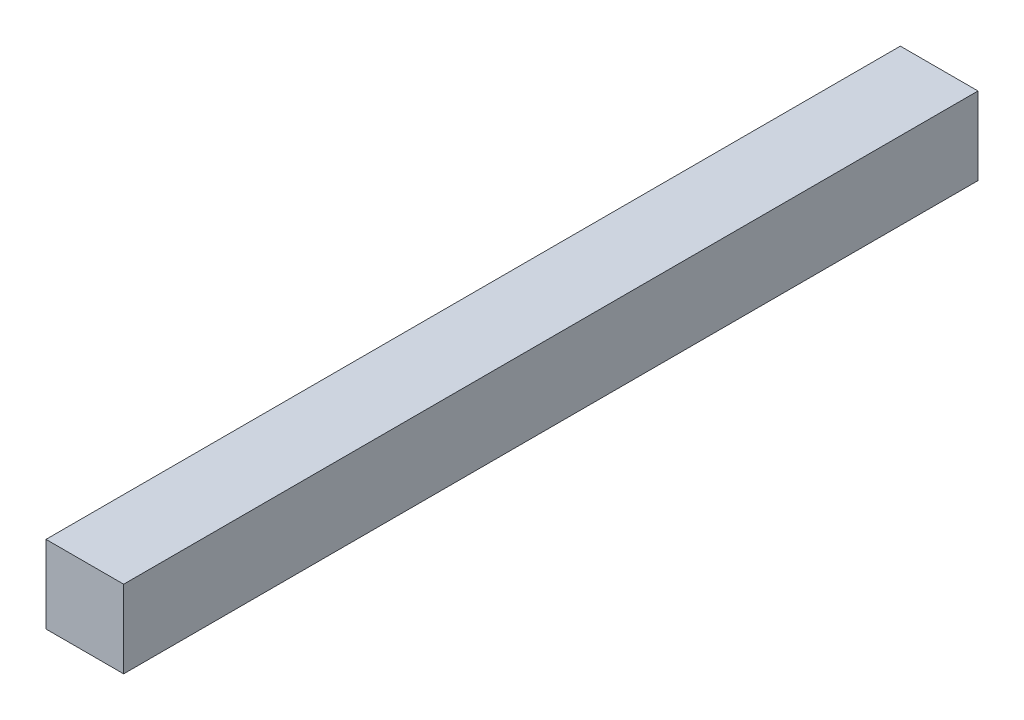
SolidWorks part; units mm, degrees
ref_plane "Front" through (0, 0, 0) normal (0, 0, 1) x (1, 0, 0)
ref_plane "Top" through (0, 0, 0) normal (0, 1, 0) x (1, 0, 0)
ref_plane "Right" through (0, 0, 0) normal (1, 0, 0) x (0, 0, -1)
sketch "Sketch1" plane through (0, 0, 0) normal (0, 0, 1) x (1, 0, 0)
  line L1 (0, 0) -> (-2.54, 0)
  line L2 (0, 0) -> (0, 2.54)
  line L3 (0, 2.54) -> (-2.54, 2.54)
  line L4 (-2.54, 0) -> (-2.54, 2.54)
  dimension "D1" = 2.54
extrude "Boss-Extrude1" add sketch "Sketch1" along normal blind 27.94
sketch "Sketch2" plane through (0, 0, 0) normal (1, 0, 0) x (0, 0, -1)
  line L0 (0, 0) -> (0, 2.54) construction
  line L1 (-27.94, 2.54) -> (0, 2.54) construction
  circle A0 centre (-1.27, 1.27) radius 0.4445
  point P2 (0, 0)
  dimension "D1" = 0.889
  dimension "D3" = 1.27
  dimension "D2" = 1.27
